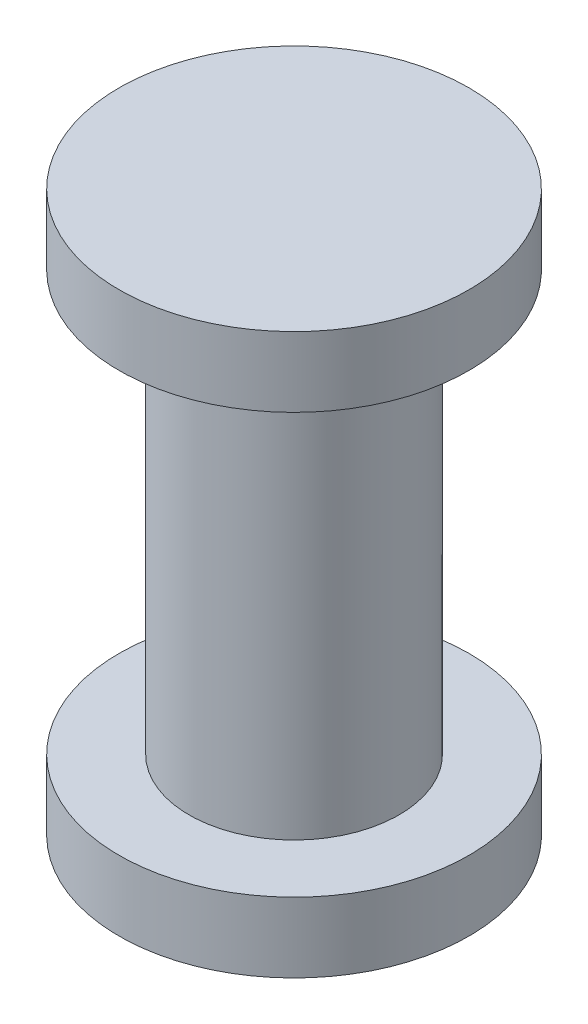
SolidWorks part; units mm, degrees
ref_plane "Front Plane" through (0, 0, 0) normal (0, 0, 1) x (1, 0, 0)
ref_plane "Top Plane" through (0, 0, 0) normal (0, 1, 0) x (1, 0, 0)
ref_plane "Right Plane" through (0, 0, 0) normal (1, 0, 0) x (0, 0, -1)
sketch "Sketch1" plane through (0, 0, 0) normal (0, 0, 1) x (1, 0, 0)
  line L0 (0, 0) -> (0, 8)
  line L1 (0, 8) -> (-2.5, 8)
  line L2 (-2.5, 8) -> (-2.5, 7)
  line L3 (-2.5, 7) -> (-1.5, 7)
  line L4 (-1.5, 7) -> (-1.5, 1)
  line L5 (-1.5, 1) -> (-2.5, 1)
  line L6 (-2.5, 1) -> (-2.5, 0)
  line L7 (-2.5, 0) -> (0, 0)
  dimension "D1" = 8
  dimension "D2" = 1
  dimension "D3" = 1
  dimension "D4" = 2.5
  dimension "D5" = 1.5
revolve "Revolve1" add sketch "Sketch1" angle 360 about L0
